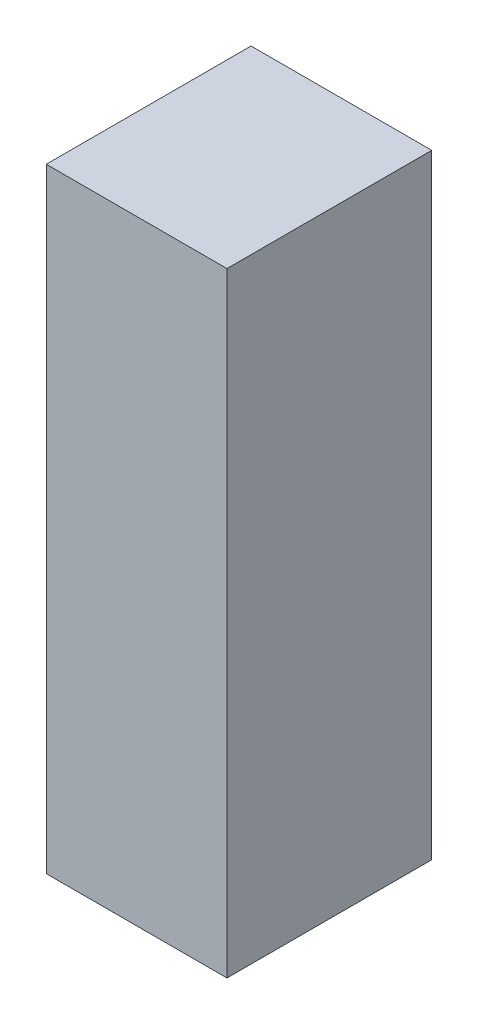
SolidWorks part; units mm, degrees
material "自定义塑料"
ref_plane "前视基准面" through (0, 0, 0) normal (0, 0, 1) x (1, 0, 0)
ref_plane "上视基准面" through (0, 0, 0) normal (0, 1, 0) x (1, 0, 0)
ref_plane "右视基准面" through (0, 0, 0) normal (1, 0, 0) x (0, 0, -1)
sketch "Sketch1" plane through (0, 0, 0) normal (0, 1, 0) x (1, 0, 0)
  line L1 (-46.8919, 10.7941) -> (-16.8919, 10.7941)
  line L2 (-46.8919, 10.7941) -> (-46.8919, -23.2059)
  line L3 (-46.8919, -23.2059) -> (-16.8919, -23.2059)
  line L4 (-16.8919, 10.7941) -> (-16.8919, -23.2059)
extrude "Extrude1" add sketch "Sketch1" along normal blind 102
